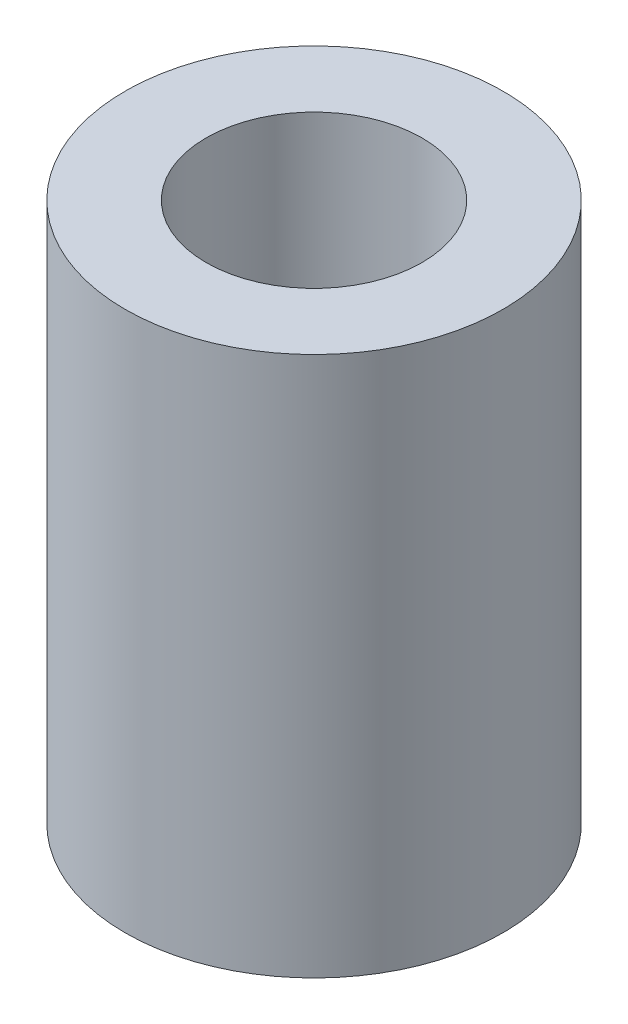
SolidWorks part; units mm, degrees
ref_plane "Front Plane" through (0, 0, 0) normal (0, 0, 1) x (1, 0, 0)
ref_plane "Top Plane" through (0, 0, 0) normal (0, 1, 0) x (1, 0, 0)
ref_plane "Right Plane" through (0, 0, 0) normal (1, 0, 0) x (0, 0, -1)
sketch "Sketch1" plane through (0, 0, 0) normal (0, 1, 0) x (1, 0, 0)
  circle A0 centre (0, 0) radius 2
  circle A1 centre (0, 0) radius 3.5
  dimension "D1" = 4
  dimension "D2" = 7
extrude "Boss-Extrude1" add sketch "Sketch1" along normal blind 10
